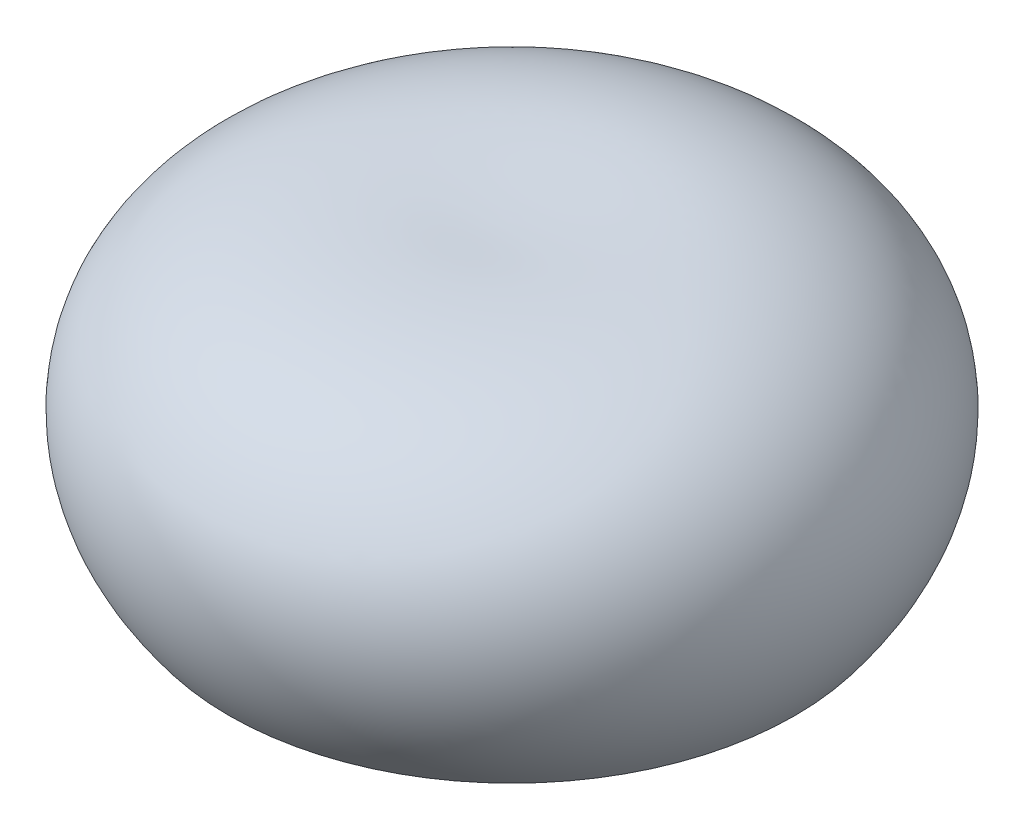
SolidWorks part; units mm, degrees
ref_plane "前视基准面" through (0, 0, 0) normal (0, 0, 1) x (1, 0, 0)
ref_plane "上视基准面" through (0, 0, 0) normal (0, 1, 0) x (1, 0, 0)
ref_plane "右视基准面" through (0, 0, 0) normal (1, 0, 0) x (0, 0, -1)
curve "曲线1"
  spline degree 3 poles (0, 7, 0) (0.0738, 6.9996, 0) (0.1783, 6.9991, 0) (0.3064, 7.0012, 0) (0.3805, 7.0029, 0) (0.4416, 7.0045, 0) (0.495, 7.0061, 0) (0.5432, 7.0077, 0) (0.5875, 7.0093, 0) (0.6288, 7.0109, 0) (0.6676, 7.0125, 0) (0.7044, 7.0141, 0) (0.7394, 7.0157, 0) (0.7729, 7.0172, 0) (0.8051, 7.0187, 0) (0.8362, 7.0203, 0) (0.8662, 7.0218, 0) (0.8953, 7.0233, 0) (0.9235, 7.0247, 0) (0.951, 7.0262, 0) (0.9778, 7.0276, 0) (1.004, 7.0291, 0) (1.0295, 7.0305, 0) (1.0545, 7.0319, 0) (1.079, 7.0333, 0) (1.103, 7.0346, 0) (1.1265, 7.036, 0) (1.1496, 7.0373, 0) (1.1724, 7.0386, 0) (1.1947, 7.0399, 0) (1.2167, 7.0412, 0) (1.2384, 7.0425, 0) (1.2598, 7.0438, 0) (1.2808, 7.045, 0) (1.3016, 7.0462, 0) (1.3221, 7.0474, 0) (1.3423, 7.0486, 0) (1.3623, 7.0498, 0) (1.382, 7.051, 0) (1.4015, 7.0521, 0) (1.4208, 7.0533, 0) (1.4399, 7.0544, 0) (1.4588, 7.0555, 0) (1.4775, 7.0566, 0) (1.496, 7.0577, 0) (1.5143, 7.0587, 0) (1.5324, 7.0598, 0) (1.5504, 7.0608, 0) (1.5682, 7.0618, 0) (1.5859, 7.0628, 0) (1.6034, 7.0638, 0) (1.6207, 7.0648, 0) (1.6379, 7.0657, 0) (1.655, 7.0667, 0) (1.672, 7.0676, 0) (1.6888, 7.0685, 0) (1.7054, 7.0694, 0) (1.722, 7.0703, 0) (1.7385, 7.0712, 0) (1.7548, 7.072, 0) (1.771, 7.0728, 0) (1.7871, 7.0737, 0) (1.8031, 7.0745, 0) (1.819, 7.0753, 0) (1.8348, 7.0761, 0) (1.8505, 7.0768, 0) (1.8661, 7.0776, 0) (1.8816, 7.0783, 0) (1.897, 7.079, 0) (1.9123, 7.0797, 0) (1.9275, 7.0804, 0) (1.9427, 7.0811, 0) (1.9578, 7.0818, 0) (1.9727, 7.0824, 0) (1.9876, 7.0831, 0) (2.0025, 7.0837, 0) (2.0172, 7.0843, 0) (2.0319, 7.0849, 0) (2.0465, 7.0855, 0) (2.061, 7.0861, 0) (2.0755, 7.0866, 0) (2.0899, 7.0872, 0) (2.1042, 7.0877, 0) (2.1184, 7.0882, 0) (2.1326, 7.0887, 0) (2.1468, 7.0892, 0) (2.1608, 7.0896, 0) (2.1748, 7.0901, 0) (2.1888, 7.0905, 0) (2.2027, 7.091, 0) (2.2165, 7.0914, 0) (2.2302, 7.0918, 0) (2.244, 7.0922, 0) (2.2576, 7.0925, 0) (2.2712, 7.0929, 0) (2.2848, 7.0933, 0) (2.2983, 7.0936, 0) (2.3117, 7.0939, 0) (2.3251, 7.0942, 0) (2.3385, 7.0945, 0) (2.3518, 7.0948, 0) (2.365, 7.095, 0) (2.3782, 7.0953, 0) (2.3914, 7.0955, 0) (2.4045, 7.0958, 0) (2.4175, 7.096, 0) (2.4305, 7.0962, 0) (2.4435, 7.0964, 0) (2.4565, 7.0965, 0) (2.4693, 7.0967, 0) (2.4822, 7.0968, 0) (2.495, 7.097, 0) (2.5078, 7.0971, 0) (2.5205, 7.0972, 0) (2.5332, 7.0973, 0) (2.5458, 7.0974, 0) (2.5584, 7.0974, 0) (2.571, 7.0975, 0) (2.5835, 7.0975, 0) (2.596, 7.0975, 0) (2.6085, 7.0975, 0) (2.6209, 7.0975, 0) (2.6333, 7.0975, 0) (2.6457, 7.0975, 0) (2.658, 7.0975, 0) (2.6703, 7.0974, 0) (2.6825, 7.0973, 0) (2.6948, 7.0973, 0) (2.7069, 7.0972, 0) (2.7191, 7.0971, 0) (2.7312, 7.0969, 0) (2.7433, 7.0968, 0) (2.7554, 7.0967, 0) (2.7674, 7.0965, 0) (2.7794, 7.0963, 0) (2.7914, 7.0962, 0) (2.8033, 7.096, 0) (2.8152, 7.0958, 0) (2.8271, 7.0955, 0) (2.8389, 7.0953, 0) (2.8508, 7.095, 0) (2.8625, 7.0948, 0) (2.8743, 7.0945, 0) (2.8861, 7.0942, 0) (2.8978, 7.0939, 0) (2.9094, 7.0936, 0) (2.9211, 7.0933, 0) (2.9327, 7.093, 0) (2.9443, 7.0926, 0) (2.9559, 7.0922, 0) (2.9675, 7.0919, 0) (2.979, 7.0915, 0) (2.9905, 7.0911, 0) (3.002, 7.0907, 0) (3.0134, 7.0902, 0) (3.0249, 7.0898, 0) (3.0363, 7.0893, 0) (3.0477, 7.0889, 0) (3.059, 7.0884, 0) (3.0704, 7.0879, 0) (3.0817, 7.0874, 0) (3.093, 7.0869, 0) (3.1042, 7.0864, 0) (3.1155, 7.0858, 0) (3.1267, 7.0853, 0) (3.1379, 7.0847, 0) (3.1491, 7.0841, 0) (3.1602, 7.0835, 0) (3.1714, 7.0829, 0) (3.1825, 7.0823, 0) (3.1936, 7.0817, 0) (3.2047, 7.0811, 0) (3.2157, 7.0804, 0) (3.2267, 7.0797, 0) (3.2378, 7.0791, 0) (3.2488, 7.0784, 0) (3.2597, 7.0777, 0) (3.2707, 7.0769, 0) (3.2816, 7.0762, 0) (3.2925, 7.0755, 0) (3.3034, 7.0747, 0) (3.3143, 7.074, 0) (3.3252, 7.0732, 0) (3.336, 7.0724, 0) (3.3468, 7.0716, 0) (3.3576, 7.0708, 0) (3.3684, 7.0699, 0) (3.3792, 7.0691, 0) (3.3899, 7.0683, 0) (3.4006, 7.0674, 0) (3.4113, 7.0665, 0) (3.422, 7.0656, 0) (3.4327, 7.0647, 0) (3.4434, 7.0638, 0) (3.454, 7.0629, 0) (3.4646, 7.0619, 0) (3.4752, 7.061, 0) (3.4858, 7.06, 0) (3.4964, 7.059, 0) (3.507, 7.0581, 0) (3.5175, 7.0571, 0) (3.528, 7.056, 0) (3.5385, 7.055, 0) (3.549, 7.054, 0) (3.5595, 7.0529, 0) (3.5699, 7.0519, 0) (3.5804, 7.0508, 0) (3.5908, 7.0497, 0) (3.6012, 7.0486, 0) (3.6116, 7.0475, 0) (3.622, 7.0464, 0) (3.6324, 7.0452, 0) (3.6427, 7.0441, 0) (3.6531, 7.0429, 0) (3.6634, 7.0417, 0) (3.6737, 7.0406, 0) (3.684, 7.0394, 0) (3.6942, 7.0381, 0) (3.7045, 7.0369, 0) (3.7148, 7.0357, 0) (3.725, 7.0344, 0) (3.7352, 7.0332, 0) (3.7454, 7.0319, 0) (3.7556, 7.0306, 0) (3.7658, 7.0293, 0) (3.7759, 7.028, 0) (3.7861, 7.0267, 0) (3.7962, 7.0254, 0) (3.8063, 7.024, 0) (3.8164, 7.0227, 0) (3.8265, 7.0213, 0) (3.8366, 7.0199, 0) (3.8467, 7.0185, 0) (3.8567, 7.0171, 0) (3.8668, 7.0157, 0) (3.8768, 7.0142, 0) (3.8868, 7.0128, 0) (3.8968, 7.0113, 0) (3.9068, 7.0099, 0) (3.9168, 7.0084, 0) (3.9267, 7.0069, 0) (3.9367, 7.0054, 0) (3.9466, 7.0039, 0) (3.9565, 7.0024, 0) (3.9665, 7.0008, 0) (3.9764, 6.9993, 0) (3.9862, 6.9977, 0) (3.9961, 6.9961, 0) (4.006, 6.9945, 0) (4.0158, 6.9929, 0) (4.0257, 6.9913, 0) (4.0355, 6.9897, 0) (4.0453, 6.988, 0) (4.0551, 6.9864, 0) (4.0649, 6.9847, 0) (4.0747, 6.983, 0) (4.0844, 6.9813, 0) (4.0942, 6.9796, 0) (4.1039, 6.9779, 0) (4.1136, 6.9762, 0) (4.1234, 6.9745, 0) (4.1331, 6.9727, 0) (4.1428, 6.971, 0) (4.1524, 6.9692, 0) (4.1621, 6.9674, 0) (4.1718, 6.9656, 0) (4.1814, 6.9638, 0) (4.1911, 6.962, 0) (4.2007, 6.9601, 0) (4.2103, 6.9583, 0) (4.2199, 6.9564, 0) (4.2295, 6.9545, 0) (4.2391, 6.9527, 0) (4.2486, 6.9508, 0) (4.2582, 6.9488, 0) (4.2677, 6.9469, 0) (4.2773, 6.945, 0) (4.2868, 6.943, 0) (4.2963, 6.9411, 0) (4.3058, 6.9391, 0) (4.3153, 6.9371, 0) (4.3248, 6.9351, 0) (4.3343, 6.9331, 0) (4.3437, 6.9311, 0) (4.3532, 6.9291, 0) (4.3626, 6.927, 0) (4.3721, 6.925, 0) (4.3815, 6.9229, 0) (4.3909, 6.9208, 0) (4.4003, 6.9187, 0) (4.4097, 6.9166, 0) (4.4191, 6.9145, 0) (4.4284, 6.9123, 0) (4.4378, 6.9102, 0) (4.4471, 6.908, 0) (4.4565, 6.9059, 0) (4.4658, 6.9037, 0) (4.4751, 6.9015, 0) (4.4844, 6.8993, 0) (4.4937, 6.8971, 0) (4.503, 6.8948, 0) (4.5123, 6.8926, 0) (4.5215, 6.8903, 0) (4.5308, 6.8881, 0) (4.54, 6.8858, 0) (4.5493, 6.8835, 0) (4.5585, 6.8812, 0) (4.5677, 6.8789, 0) (4.5769, 6.8765, 0) (4.5861, 6.8742, 0) (4.5953, 6.8718, 0) (4.6045, 6.8695, 0) (4.6136, 6.8671, 0) (4.6228, 6.8647, 0) (4.6319, 6.8623, 0) (4.6411, 6.8599, 0) (4.6502, 6.8575, 0) (4.6593, 6.855, 0) (4.6684, 6.8526, 0) (4.6775, 6.8501, 0) (4.6866, 6.8476, 0) (4.6957, 6.8451, 0) (4.7048, 6.8426, 0) (4.7138, 6.8401, 0) (4.7229, 6.8376, 0) (4.7319, 6.835, 0) (4.741, 6.8325, 0) (4.75, 6.8299, 0) (4.759, 6.8273, 0) (4.768, 6.8247, 0) (4.777, 6.8221, 0) (4.786, 6.8195, 0) (4.795, 6.8169, 0) (4.8039, 6.8142, 0) (4.8129, 6.8116, 0) (4.8218, 6.8089, 0) (4.8308, 6.8062, 0) (4.8397, 6.8035, 0) (4.8486, 6.8008, 0) (4.8575, 6.7981, 0) (4.8664, 6.7954, 0) (4.8753, 6.7926, 0) (4.8842, 6.7899, 0) (4.8931, 6.7871, 0) (4.902, 6.7843, 0) (4.9108, 6.7815, 0) (4.9197, 6.7787, 0) (4.9285, 6.7759, 0) (4.9373, 6.7731, 0) (4.9462, 6.7702, 0) (4.955, 6.7673, 0) (4.9638, 6.7645, 0) (4.9726, 6.7616, 0) (4.9813, 6.7587, 0) (4.9901, 6.7558, 0) (4.9989, 6.7529, 0) (5.0076, 6.7499, 0) (5.0164, 6.747, 0) (5.0251, 6.744, 0) (5.0339, 6.7411, 0) (5.0426, 6.7381, 0) (5.0513, 6.7351, 0) (5.06, 6.7321, 0) (5.0687, 6.729, 0) (5.0774, 6.726, 0) (5.0861, 6.7229, 0) (5.0947, 6.7199, 0) (5.1034, 6.7168, 0) (5.112, 6.7137, 0) (5.1207, 6.7106, 0) (5.1293, 6.7075, 0) (5.1379, 6.7044, 0) (5.1465, 6.7012, 0) (5.1552, 6.6981, 0) (5.1638, 6.6949, 0) (5.1723, 6.6917, 0) (5.1809, 6.6885, 0) (5.1895, 6.6853, 0) (5.1981, 6.6821, 0) (5.2066, 6.6789, 0) (5.2151, 6.6756, 0) (5.2237, 6.6724, 0) (5.2322, 6.6691, 0) (5.2407, 6.6658, 0) (5.2492, 6.6625, 0) (5.2577, 6.6592, 0) (5.2662, 6.6559, 0) (5.2747, 6.6526, 0) (5.2832, 6.6492, 0) (5.2917, 6.6459, 0) (5.3001, 6.6425, 0) (5.3086, 6.6391, 0) (5.317, 6.6357, 0) (5.3254, 6.6323, 0) (5.3338, 6.6289, 0) (5.3423, 6.6254, 0) (5.3507, 6.622, 0) (5.3591, 6.6185, 0) (5.3674, 6.615, 0) (5.3758, 6.6115, 0) (5.3842, 6.608, 0) (5.3926, 6.6045, 0) (5.4009, 6.601, 0) (5.4092, 6.5974, 0) (5.4176, 6.5939, 0) (5.4259, 6.5903, 0) (5.4342, 6.5867, 0) (5.4425, 6.5831, 0) (5.4508, 6.5795, 0) (5.4591, 6.5759, 0) (5.4674, 6.5722, 0) (5.4757, 6.5686, 0) (5.4839, 6.5649, 0) (5.4922, 6.5612, 0) (5.5004, 6.5576, 0) (5.5087, 6.5538, 0) (5.5169, 6.5501, 0) (5.5251, 6.5464, 0) (5.5333, 6.5427, 0) (5.5415, 6.5389, 0) (5.5497, 6.5351, 0) (5.5579, 6.5313, 0) (5.5661, 6.5275, 0) (5.5743, 6.5237, 0) (5.5824, 6.5199, 0) (5.5906, 6.5161, 0) (5.5987, 6.5122, 0) (5.6069, 6.5083, 0) (5.615, 6.5045, 0) (5.6231, 6.5006, 0) (5.6312, 6.4967, 0) (5.6393, 6.4927, 0) (5.6474, 6.4888, 0) (5.6555, 6.4849, 0) (5.6635, 6.4809, 0) (5.6716, 6.4769, 0) (5.6796, 6.4729, 0) (5.6877, 6.4689, 0) (5.6957, 6.4649, 0) (5.7038, 6.4609, 0) (5.7118, 6.4568, 0) (5.7198, 6.4528, 0) (5.7278, 6.4487, 0) (5.7358, 6.4446, 0) (5.7438, 6.4405, 0) (5.7517, 6.4364, 0) (5.7597, 6.4323, 0) (5.7676, 6.4282, 0) (5.7756, 6.424, 0) (5.7835, 6.4198, 0) (5.7915, 6.4157, 0) (5.7994, 6.4115, 0) (5.8073, 6.4073, 0) (5.8152, 6.403, 0) (5.8231, 6.3988, 0) (5.831, 6.3945, 0) (5.8388, 6.3903, 0) (5.8467, 6.386, 0) (5.8546, 6.3817, 0) (5.8624, 6.3774, 0) (5.8703, 6.3731, 0) (5.8781, 6.3687, 0) (5.8859, 6.3644, 0) (5.8937, 6.36, 0) (5.9015, 6.3557, 0) (5.9093, 6.3513, 0) (5.9171, 6.3469, 0) (5.9249, 6.3424, 0) (5.9326, 6.338, 0) (5.9404, 6.3336, 0) (5.9481, 6.3291, 0) (5.9559, 6.3246, 0) (5.9636, 6.3201, 0) (5.9713, 6.3156, 0) (5.979, 6.3111, 0) (5.9867, 6.3066, 0) (5.9944, 6.302, 0) (6.0021, 6.2975, 0) (6.0098, 6.2929, 0) (6.0175, 6.2883, 0) (6.0251, 6.2837, 0) (6.0328, 6.2791, 0) (6.0404, 6.2745, 0) (6.048, 6.2698, 0) (6.0556, 6.2652, 0) (6.0633, 6.2605, 0) (6.0709, 6.2558, 0) (6.0784, 6.2511, 0) (6.086, 6.2464, 0) (6.0936, 6.2416, 0) (6.1012, 6.2369, 0) (6.1087, 6.2321, 0) (6.1163, 6.2274, 0) (6.1238, 6.2226, 0) (6.1313, 6.2178, 0) (6.1388, 6.2129, 0) (6.1463, 6.2081, 0) (6.1538, 6.2033, 0) (6.1613, 6.1984, 0) (6.1688, 6.1935, 0) (6.1763, 6.1886, 0) (6.1837, 6.1837, 0) (6.1912, 6.1788, 0) (6.1986, 6.1739, 0) (6.206, 6.1689, 0) (6.2134, 6.1639, 0) (6.2208, 6.159, 0) (6.2282, 6.154, 0) (6.2356, 6.1489, 0) (6.243, 6.1439, 0) (6.2504, 6.1389, 0) (6.2577, 6.1338, 0) (6.2651, 6.1287, 0) (6.2724, 6.1237, 0) (6.2798, 6.1186, 0) (6.2871, 6.1134, 0) (6.2944, 6.1083, 0) (6.3017, 6.1032, 0) (6.309, 6.098, 0) (6.3163, 6.0928, 0) (6.3235, 6.0876, 0) (6.3308, 6.0824, 0) (6.3381, 6.0772, 0) (6.3453, 6.072, 0) (6.3525, 6.0667, 0) (6.3598, 6.0615, 0) (6.367, 6.0562, 0) (6.3742, 6.0509, 0) (6.3814, 6.0456, 0) (6.3885, 6.0403, 0) (6.3957, 6.0349, 0) (6.4029, 6.0296, 0) (6.41, 6.0242, 0) (6.4172, 6.0188, 0) (6.4243, 6.0134, 0) (6.4314, 6.008, 0) (6.4385, 6.0025, 0) (6.4456, 5.9971, 0) (6.4527, 5.9916, 0) (6.4598, 5.9861, 0) (6.4668, 5.9806, 0) (6.4739, 5.9751, 0) (6.4809, 5.9696, 0) (6.488, 5.9641, 0) (6.495, 5.9585, 0) (6.502, 5.9529, 0) (6.509, 5.9473, 0) (6.516, 5.9417, 0) (6.523, 5.9361, 0) (6.53, 5.9305, 0) (6.5369, 5.9248, 0) (6.5439, 5.9192, 0) (6.5508, 5.9135, 0) (6.5578, 5.9078, 0) (6.5647, 5.9021, 0) (6.5716, 5.8963, 0) (6.5785, 5.8906, 0) (6.5854, 5.8848, 0) (6.5922, 5.8791, 0) (6.5991, 5.8733, 0) (6.606, 5.8675, 0) (6.6128, 5.8616, 0) (6.6196, 5.8558, 0) (6.6265, 5.8499, 0) (6.6333, 5.8441, 0) (6.6401, 5.8382, 0) (6.6469, 5.8323, 0) (6.6536, 5.8263, 0) (6.6604, 5.8204, 0) (6.6672, 5.8144, 0) (6.6739, 5.8085, 0) (6.6806, 5.8025, 0) (6.6874, 5.7965, 0) (6.6941, 5.7905, 0) (6.7008, 5.7844, 0) (6.7074, 5.7784, 0) (6.7141, 5.7723, 0) (6.7208, 5.7662, 0) (6.7274, 5.7601, 0) (6.7341, 5.754, 0) (6.7407, 5.7479, 0) (6.7473, 5.7417, 0) (6.7539, 5.7356, 0) (6.7605, 5.7294, 0) (6.7671, 5.7232, 0) (6.7737, 5.717, 0) (6.7802, 5.7107, 0) (6.7868, 5.7045, 0) (6.7933, 5.6982, 0) (6.7998, 5.6919, 0) (6.8064, 5.6856, 0) (6.8129, 5.6793, 0) (6.8194, 5.673, 0) (6.8258, 5.6666, 0) (6.8323, 5.6603, 0) (6.8387, 5.6539, 0) (6.8452, 5.6475, 0) (6.8516, 5.6411, 0) (6.858, 5.6346, 0) (6.8644, 5.6282, 0) (6.8708, 5.6217, 0) (6.8772, 5.6152, 0) (6.8836, 5.6087, 0) (6.8899, 5.6022, 0) (6.8963, 5.5957, 0) (6.9026, 5.5891, 0) (6.9089, 5.5825, 0) (6.9152, 5.5759, 0) (6.9215, 5.5693, 0) (6.9278, 5.5627, 0) (6.9341, 5.5561, 0) (6.9403, 5.5494, 0) (6.9466, 5.5427, 0) (6.9528, 5.5361, 0) (6.959, 5.5293, 0) (6.9652, 5.5226, 0) (6.9714, 5.5159, 0) (6.9776, 5.5091, 0) (6.9838, 5.5023, 0) (6.9899, 5.4955, 0) (6.9961, 5.4887, 0) (7.0022, 5.4819, 0) (7.0083, 5.475, 0) (7.0144, 5.4682, 0) (7.0205, 5.4613, 0) (7.0266, 5.4544, 0) (7.0326, 5.4475, 0) (7.0387, 5.4405, 0) (7.0447, 5.4336, 0) (7.0507, 5.4266, 0) (7.0568, 5.4196, 0) (7.0627, 5.4126, 0) (7.0687, 5.4055, 0) (7.0747, 5.3985, 0) (7.0807, 5.3914, 0) (7.0866, 5.3844, 0) (7.0925, 5.3772, 0) (7.0984, 5.3701, 0) (7.1043, 5.363, 0) (7.1102, 5.3558, 0) (7.1161, 5.3487, 0) (7.122, 5.3415, 0) (7.1278, 5.3343, 0) (7.1336, 5.327, 0) (7.1395, 5.3198, 0) (7.1453, 5.3125, 0) (7.151, 5.3052, 0) (7.1568, 5.2979, 0) (7.1626, 5.2906, 0) (7.1683, 5.2833, 0) (7.1741, 5.2759, 0) (7.1798, 5.2685, 0) (7.1855, 5.2611, 0) (7.1912, 5.2537, 0) (7.1968, 5.2463, 0) (7.2025, 5.2388, 0) (7.2082, 5.2313, 0) (7.2138, 5.2238, 0) (7.2194, 5.2163, 0) (7.225, 5.2088, 0) (7.2306, 5.2013, 0) (7.2362, 5.1937, 0) (7.2417, 5.1861, 0) (7.2473, 5.1785, 0) (7.2528, 5.1709, 0) (7.2583, 5.1632, 0) (7.2638, 5.1556, 0) (7.2693, 5.1479, 0) (7.2748, 5.1402, 0) (7.2802, 5.1324, 0) (7.2856, 5.1247, 0) (7.2911, 5.1169, 0) (7.2965, 5.1092, 0) (7.3019, 5.1014, 0) (7.3072, 5.0935, 0) (7.3126, 5.0857, 0) (7.3179, 5.0778, 0) (7.3233, 5.0699, 0) (7.3286, 5.062, 0) (7.3339, 5.0541, 0) (7.3391, 5.0462, 0) (7.3444, 5.0382, 0) (7.3497, 5.0302, 0) (7.3549, 5.0222, 0) (7.3601, 5.0142, 0) (7.3653, 5.0062, 0) (7.3705, 4.9981, 0) (7.3757, 4.99, 0) (7.3808, 4.9819, 0) (7.3859, 4.9738, 0) (7.3911, 4.9657, 0) (7.3962, 4.9575, 0) (7.4012, 4.9493, 0) (7.4063, 4.9411, 0) (7.4114, 4.9329, 0) (7.4164, 4.9246, 0) (7.4214, 4.9164, 0) (7.4264, 4.9081, 0) (7.4314, 4.8998, 0) (7.4364, 4.8914, 0) (7.4413, 4.8831, 0) (7.4462, 4.8747, 0) (7.4512, 4.8663, 0) (7.4561, 4.8579, 0) (7.4609, 4.8495, 0) (7.4658, 4.841, 0) (7.4706, 4.8325, 0) (7.4755, 4.824, 0) (7.4803, 4.8155, 0) (7.4851, 4.807, 0) (7.4899, 4.7984, 0) (7.4946, 4.7898, 0) (7.4993, 4.7812, 0) (7.5041, 4.7726, 0) (7.5088, 4.7639, 0) (7.5134, 4.7552, 0) (7.5181, 4.7465, 0) (7.5228, 4.7378, 0) (7.5274, 4.7291, 0) (7.532, 4.7203, 0) (7.5366, 4.7115, 0) (7.5412, 4.7027, 0) (7.5457, 4.6939, 0) (7.5503, 4.6851, 0) (7.5548, 4.6762, 0) (7.5593, 4.6673, 0) (7.5637, 4.6584, 0) (7.5682, 4.6494, 0) (7.5726, 4.6405, 0) (7.5771, 4.6315, 0) (7.5815, 4.6225, 0) (7.5858, 4.6134, 0) (7.5902, 4.6044, 0) (7.5945, 4.5953, 0) (7.5989, 4.5862, 0) (7.6032, 4.5771, 0) (7.6075, 4.5679, 0) (7.6117, 4.5587, 0) (7.616, 4.5495, 0) (7.6202, 4.5403, 0) (7.6244, 4.5311, 0) (7.6286, 4.5218, 0) (7.6327, 4.5125, 0) (7.6369, 4.5032, 0) (7.641, 4.4939, 0) (7.6451, 4.4845, 0) (7.6492, 4.4751, 0) (7.6532, 4.4657, 0) (7.6573, 4.4563, 0) (7.6613, 4.4468, 0) (7.6653, 4.4373, 0) (7.6692, 4.4278, 0) (7.6732, 4.4183, 0) (7.6771, 4.4087, 0) (7.681, 4.3992, 0) (7.6849, 4.3896, 0) (7.6888, 4.3799, 0) (7.6926, 4.3703, 0) (7.6964, 4.3606, 0) (7.7002, 4.3509, 0) (7.704, 4.3411, 0) (7.7078, 4.3314, 0) (7.7115, 4.3216, 0) (7.7152, 4.3118, 0) (7.7189, 4.302, 0) (7.7226, 4.2921, 0) (7.7262, 4.2822, 0) (7.7298, 4.2723, 0) (7.7334, 4.2624, 0) (7.737, 4.2524, 0) (7.7405, 4.2424, 0) (7.744, 4.2324, 0) (7.7475, 4.2223, 0) (7.751, 4.2123, 0) (7.7545, 4.2022, 0) (7.7579, 4.1921, 0) (7.7613, 4.1819, 0) (7.7647, 4.1717, 0) (7.768, 4.1615, 0) (7.7714, 4.1513, 0) (7.7747, 4.141, 0) (7.778, 4.1308, 0) (7.7812, 4.1204, 0) (7.7845, 4.1101, 0) (7.7877, 4.0997, 0) (7.7908, 4.0893, 0) (7.794, 4.0789, 0) (7.7971, 4.0685, 0) (7.8002, 4.058, 0) (7.8033, 4.0475, 0) (7.8064, 4.0369, 0) (7.8094, 4.0264, 0) (7.8124, 4.0158, 0) (7.8154, 4.0051, 0) (7.8183, 3.9945, 0) (7.8212, 3.9838, 0) (7.8241, 3.9731, 0) (7.827, 3.9624, 0) (7.8298, 3.9516, 0) (7.8327, 3.9408, 0) (7.8354, 3.93, 0) (7.8382, 3.9191, 0) (7.8409, 3.9082, 0) (7.8436, 3.8973, 0) (7.8463, 3.8863, 0) (7.849, 3.8754, 0) (7.8516, 3.8643, 0) (7.8542, 3.8533, 0) (7.8567, 3.8422, 0) (7.8593, 3.8311, 0) (7.8618, 3.82, 0) (7.8642, 3.8088, 0) (7.8667, 3.7976, 0) (7.8691, 3.7864, 0) (7.8715, 3.7751, 0) (7.8738, 3.7638, 0) (7.8762, 3.7525, 0) (7.8785, 3.7411, 0) (7.8807, 3.7297, 0) (7.883, 3.7183, 0) (7.8852, 3.7069, 0) (7.8873, 3.6954, 0) (7.8895, 3.6838, 0) (7.8916, 3.6723, 0) (7.8937, 3.6607, 0) (7.8957, 3.6491, 0) (7.8977, 3.6374, 0) (7.8997, 3.6257, 0) (7.9016, 3.614, 0) (7.9036, 3.6022, 0) (7.9054, 3.5904, 0) (7.9073, 3.5786, 0) (7.9091, 3.5667, 0) (7.9109, 3.5548, 0) (7.9126, 3.5429, 0) (7.9144, 3.5309, 0) (7.916, 3.5189, 0) (7.9177, 3.5068, 0) (7.9193, 3.4947, 0) (7.9209, 3.4826, 0) (7.9224, 3.4705, 0) (7.9239, 3.4583, 0) (7.9254, 3.446, 0) (7.9268, 3.4338, 0) (7.9282, 3.4214, 0) (7.9296, 3.4091, 0) (7.9309, 3.3967, 0) (7.9322, 3.3843, 0) (7.9334, 3.3718, 0) (7.9346, 3.3593, 0) (7.9358, 3.3468, 0) (7.9369, 3.3342, 0) (7.938, 3.3215, 0) (7.9391, 3.3089, 0) (7.9401, 3.2962, 0) (7.9411, 3.2834, 0) (7.942, 3.2706, 0) (7.9429, 3.2578, 0) (7.9438, 3.2449, 0) (7.9446, 3.232, 0) (7.9454, 3.219, 0) (7.9461, 3.206, 0) (7.9468, 3.193, 0) (7.9475, 3.1799, 0) (7.9481, 3.1668, 0) (7.9486, 3.1536, 0) (7.9492, 3.1403, 0) (7.9496, 3.1271, 0) (7.9501, 3.1138, 0) (7.9505, 3.1004, 0) (7.9508, 3.087, 0) (7.9511, 3.0735, 0) (7.9514, 3.06, 0) (7.9516, 3.0465, 0) (7.9517, 3.0329, 0) (7.9518, 3.0192, 0) (7.9519, 3.0055, 0) (7.9519, 2.9918, 0) (7.9519, 2.978, 0) (7.9518, 2.9641, 0) (7.9517, 2.9502, 0) (7.9515, 2.9363, 0) (7.9513, 2.9223, 0) (7.951, 2.9082, 0) (7.9507, 2.8941, 0) (7.9503, 2.88, 0) (7.9499, 2.8657, 0) (7.9494, 2.8515, 0) (7.9489, 2.8371, 0) (7.9483, 2.8228, 0) (7.9477, 2.8083, 0) (7.947, 2.7938, 0) (7.9462, 2.7793, 0) (7.9454, 2.7647, 0) (7.9445, 2.75, 0) (7.9436, 2.7353, 0) (7.9426, 2.7205, 0) (7.9416, 2.7056, 0) (7.9405, 2.6907, 0) (7.9393, 2.6757, 0) (7.9381, 2.6607, 0) (7.9368, 2.6456, 0) (7.9355, 2.6304, 0) (7.9341, 2.6152, 0) (7.9326, 2.5999, 0) (7.9311, 2.5845, 0) (7.9295, 2.5691, 0) (7.9278, 2.5536, 0) (7.9261, 2.538, 0) (7.9243, 2.5224, 0) (7.9224, 2.5066, 0) (7.9205, 2.4909, 0) (7.9185, 2.475, 0) (7.9164, 2.459, 0) (7.9143, 2.443, 0) (7.912, 2.4269, 0) (7.9097, 2.4108, 0) (7.9074, 2.3945, 0) (7.9049, 2.3782, 0) (7.9024, 2.3618, 0) (7.8998, 2.3453, 0) (7.8971, 2.3287, 0) (7.8943, 2.312, 0) (7.8915, 2.2953, 0) (7.8885, 2.2784, 0) (7.8855, 2.2615, 0) (7.8824, 2.2445, 0) (7.8792, 2.2273, 0) (7.8759, 2.2101, 0) (7.8725, 2.1928, 0) (7.8691, 2.1754, 0) (7.8655, 2.1579, 0) (7.8618, 2.1403, 0) (7.8581, 2.1225, 0) (7.8542, 2.1047, 0) (7.8503, 2.0868, 0) (7.8462, 2.0687, 0) (7.842, 2.0506, 0) (7.8378, 2.0323, 0) (7.8334, 2.0139, 0) (7.8289, 1.9954, 0) (7.8243, 1.9767, 0) (7.8195, 1.9579, 0) (7.8147, 1.939, 0) (7.8097, 1.92, 0) (7.8046, 1.9008, 0) (7.7994, 1.8815, 0) (7.794, 1.8621, 0) (7.7885, 1.8425, 0) (7.7829, 1.8227, 0) (7.7771, 1.8028, 0) (7.7712, 1.7828, 0) (7.7652, 1.7626, 0) (7.759, 1.7422, 0) (7.7526, 1.7216, 0) (7.7461, 1.7009, 0) (7.7394, 1.6799, 0) (7.7325, 1.6588, 0) (7.7255, 1.6375, 0) (7.7182, 1.616, 0) (7.7108, 1.5943, 0) (7.7032, 1.5723, 0) (7.6954, 1.5502, 0) (7.6874, 1.5278, 0) (7.6792, 1.5051, 0) (7.6708, 1.4822, 0) (7.6621, 1.4591, 0) (7.6532, 1.4357, 0) (7.644, 1.412, 0) (7.6346, 1.388, 0) (7.6249, 1.3637, 0) (7.615, 1.3391, 0) (7.6047, 1.3141, 0) (7.5941, 1.2888, 0) (7.5833, 1.2631, 0) (7.572, 1.237, 0) (7.5604, 1.2105, 0) (7.5485, 1.1835, 0) (7.5361, 1.1561, 0) (7.5233, 1.1282, 0) (7.51, 1.0997, 0) (7.4963, 1.0707, 0) (7.482, 1.041, 0) (7.4672, 1.0107, 0) (7.4518, 0.9797, 0) (7.4357, 0.9478, 0) (7.4189, 0.9152, 0) (7.4013, 0.8815, 0) (7.3829, 0.8469, 0) (7.3635, 0.811, 0) (7.343, 0.7739, 0) (7.3212, 0.7352, 0) (7.2981, 0.6948, 0) (7.2732, 0.6523, 0) (7.2464, 0.6073, 0) (7.2172, 0.5594, 0) (7.1849, 0.5076, 0) (7.1485, 0.4506, 0) (7.1062, 0.386, 0) (7.0539, 0.3086, 0) (6.9626, 0.1779, 0) (6.8856, 0.0734, 0) (6.8314, 0, 0) knots 0 0 0 0 0.016508 0.023364 0.028636 0.033092 0.037026 0.040591 0.043877 0.046942 0.049828 0.052563 0.055171 0.057668 0.060068 0.062382 0.06462 0.066789 0.068896 0.070946 0.072944 0.074894 0.0768 0.078664 0.080491 0.082282 0.08404 0.085766 0.087463 0.089131 0.090774 0.092392 0.093986 0.095557 0.097107 0.098637 0.100147 0.101639 0.103112 0.104569 0.10601 0.107434 0.108844 0.110239 0.11162 0.112987 0.114341 0.115683 0.117013 0.118331 0.119637 0.120933 0.122218 0.123492 0.124757 0.126012 0.127257 0.128493 0.129721 0.130939 0.132149 0.133351 0.134545 0.135731 0.13691 0.138081 0.139245 0.140402 0.141552 0.142695 0.143832 0.144962 0.146086 0.147204 0.148315 0.149421 0.150522 0.151616 0.152705 0.153789 0.154868 0.155941 0.157009 0.158072 0.159131 0.160184 0.161233 0.162277 0.163317 0.164352 0.165383 0.16641 0.167433 0.168451 0.169465 0.170476 0.171482 0.172485 0.173483 0.174478 0.17547 0.176457 0.177442 0.178422 0.1794 0.180374 0.181344 0.182312 0.183276 0.184236 0.185194 0.186149 0.187101 0.188049 0.188995 0.189938 0.190877 0.191815 0.192749 0.19368 0.194609 0.195535 0.196459 0.19738 0.198298 0.199214 0.200127 0.201038 0.201946 0.202852 0.203756 0.204657 0.205556 0.206453 0.207347 0.208239 0.209129 0.210017 0.210902 0.211786 0.212667 0.213547 0.214424 0.215299 0.216172 0.217044 0.217913 0.21878 0.219646 0.220509 0.221371 0.222231 0.223089 0.223945 0.2248 0.225652 0.226503 0.227353 0.2282 0.229046 0.22989 0.230732 0.231573 0.232412 0.23325 0.234086 0.23492 0.235753 0.236585 0.237414 0.238243 0.239069 0.239895 0.240719 0.241541 0.242362 0.243182 0.244 0.244816 0.245632 0.246446 0.247258 0.24807 0.24888 0.249688 0.250496 0.251302 0.252106 0.25291 0.253712 0.254513 0.255313 0.256111 0.256909 0.257705 0.2585 0.259294 0.260086 0.260878 0.261668 0.262457 0.263245 0.264032 0.264818 0.265603 0.266386 0.267169 0.26795 0.268731 0.26951 0.270288 0.271066 0.271842 0.272617 0.273391 0.274165 0.274937 0.275708 0.276478 0.277248 0.278016 0.278784 0.27955 0.280316 0.28108 0.281844 0.282607 0.283369 0.28413 0.28489 0.285649 0.286407 0.287165 0.287921 0.288677 0.289432 0.290186 0.290939 0.291692 0.292444 0.293194 0.293944 0.294693 0.295442 0.296189 0.296936 0.297682 0.298428 0.299172 0.299916 0.300659 0.301401 0.302143 0.302883 0.303624 0.304363 0.305101 0.305839 0.306577 0.307313 0.308049 0.308784 0.309518 0.310252 0.310985 0.311718 0.312449 0.31318 0.313911 0.31464 0.31537 0.316098 0.316826 0.317553 0.31828 0.319006 0.319731 0.320456 0.32118 0.321903 0.322626 0.323349 0.32407 0.324791 0.325512 0.326232 0.326951 0.32767 0.328389 0.329106 0.329824 0.33054 0.331256 0.331972 0.332687 0.333401 0.334115 0.334829 0.335541 0.336254 0.336966 0.337677 0.338388 0.339098 0.339808 0.340517 0.341226 0.341934 0.342642 0.34335 0.344057 0.344763 0.345469 0.346174 0.346879 0.347584 0.348288 0.348992 0.349695 0.350398 0.3511 0.351802 0.352503 0.353204 0.353905 0.354605 0.355305 0.356004 0.356703 0.357401 0.3581 0.358797 0.359494 0.360191 0.360888 0.361584 0.362279 0.362975 0.36367 0.364364 0.365058 0.365752 0.366445 0.367138 0.367831 0.368523 0.369215 0.369907 0.370598 0.371289 0.371979 0.372669 0.373359 0.374049 0.374738 0.375427 0.376115 0.376803 0.377491 0.378178 0.378866 0.379552 0.380239 0.380925 0.381611 0.382297 0.382982 0.383667 0.384351 0.385036 0.38572 0.386404 0.387087 0.38777 0.388453 0.389136 0.389818 0.3905 0.391182 0.391863 0.392545 0.393226 0.393906 0.394587 0.395267 0.395947 0.396627 0.397306 0.397985 0.398664 0.399343 0.400021 0.400699 0.401377 0.402055 0.402733 0.40341 0.404087 0.404764 0.40544 0.406117 0.406793 0.407469 0.408144 0.40882 0.409495 0.41017 0.410845 0.41152 0.412194 0.412868 0.413542 0.414216 0.41489 0.415563 0.416237 0.41691 0.417583 0.418255 0.418928 0.4196 0.420273 0.420945 0.421616 0.422288 0.42296 0.423631 0.424302 0.424973 0.425644 0.426315 0.426986 0.427656 0.428326 0.428997 0.429667 0.430336 0.431006 0.431676 0.432345 0.433015 0.433684 0.434353 0.435022 0.435691 0.436359 0.437028 0.437696 0.438365 0.439033 0.439701 0.440369 0.441037 0.441705 0.442373 0.44304 0.443708 0.444375 0.445043 0.44571 0.446377 0.447044 0.447711 0.448378 0.449045 0.449711 0.450378 0.451045 0.451711 0.452378 0.453044 0.45371 0.454377 0.455043 0.455709 0.456375 0.457041 0.457707 0.458373 0.459039 0.459705 0.460371 0.461036 0.461702 0.462368 0.463034 0.463699 0.464365 0.46503 0.465696 0.466361 0.467027 0.467692 0.468358 0.469023 0.469689 0.470354 0.47102 0.471685 0.472351 0.473016 0.473681 0.474347 0.475012 0.475678 0.476343 0.477009 0.477674 0.47834 0.479005 0.479671 0.480336 0.481002 0.481668 0.482333 0.482999 0.483665 0.48433 0.484996 0.485662 0.486328 0.486994 0.48766 0.488326 0.488992 0.489658 0.490324 0.490991 0.491657 0.492324 0.49299 0.493657 0.494323 0.49499 0.495657 0.496324 0.496991 0.497658 0.498325 0.498992 0.499659 0.500327 0.500994 0.501662 0.50233 0.502997 0.503665 0.504333 0.505001 0.50567 0.506338 0.507007 0.507675 0.508344 0.509013 0.509682 0.510351 0.511021 0.51169 0.51236 0.513029 0.513699 0.514369 0.515039 0.51571 0.51638 0.517051 0.517722 0.518393 0.519064 0.519735 0.520407 0.521078 0.52175 0.522422 0.523095 0.523767 0.52444 0.525113 0.525786 0.526459 0.527132 0.527806 0.52848 0.529154 0.529828 0.530502 0.531177 0.531852 0.532527 0.533203 0.533878 0.534554 0.53523 0.535907 0.536583 0.53726 0.537937 0.538614 0.539292 0.53997 0.540648 0.541327 0.542005 0.542684 0.543363 0.544043 0.544723 0.545403 0.546083 0.546764 0.547445 0.548126 0.548808 0.549489 0.550172 0.550854 0.551537 0.55222 0.552904 0.553587 0.554271 0.554956 0.555641 0.556326 0.557011 0.557697 0.558383 0.55907 0.559757 0.560444 0.561132 0.56182 0.562508 0.563197 0.563886 0.564576 0.565266 0.565956 0.566647 0.567338 0.568029 0.568721 0.569414 0.570107 0.5708 0.571493 0.572188 0.572882 0.573577 0.574272 0.574968 0.575665 0.576361 0.577059 0.577756 0.578454 0.579153 0.579852 0.580552 0.581252 0.581952 0.582653 0.583355 0.584057 0.58476 0.585463 0.586166 0.586871 0.587575 0.58828 0.588986 0.589692 0.590399 0.591107 0.591815 0.592523 0.593232 0.593942 0.594652 0.595363 0.596074 0.596786 0.597499 0.598212 0.598926 0.59964 0.600355 0.601071 0.601787 0.602504 0.603222 0.60394 0.604659 0.605379 0.606099 0.60682 0.607541 0.608264 0.608987 0.60971 0.610435 0.61116 0.611885 0.612612 0.613339 0.614067 0.614796 0.615525 0.616255 0.616986 0.617718 0.61845 0.619183 0.619917 0.620652 0.621388 0.622124 0.622861 0.623599 0.624338 0.625078 0.625818 0.62656 0.627302 0.628045 0.628789 0.629534 0.630279 0.631026 0.631773 0.632522 0.633271 0.634021 0.634772 0.635524 0.636277 0.637031 0.637786 0.638542 0.639299 0.640056 0.640815 0.641575 0.642336 0.643098 0.64386 0.644624 0.645389 0.646155 0.646922 0.64769 0.648459 0.64923 0.650001 0.650773 0.651547 0.652322 0.653098 0.653875 0.654653 0.655432 0.656212 0.656994 0.657777 0.658561 0.659346 0.660133 0.66092 0.661709 0.662499 0.663291 0.664084 0.664878 0.665673 0.66647 0.667268 0.668067 0.668868 0.66967 0.670473 0.671278 0.672084 0.672892 0.673701 0.674511 0.675323 0.676136 0.676951 0.677768 0.678585 0.679405 0.680225 0.681048 0.681872 0.682697 0.683524 0.684353 0.685183 0.686015 0.686849 0.687684 0.688521 0.689359 0.690199 0.691041 0.691885 0.692731 0.693578 0.694427 0.695278 0.69613 0.696985 0.697841 0.698699 0.699559 0.700421 0.701285 0.702151 0.703018 0.703888 0.70476 0.705634 0.706509 0.707387 0.708267 0.709149 0.710033 0.710919 0.711808 0.712698 0.713591 0.714486 0.715384 0.716283 0.717185 0.718089 0.718996 0.719905 0.720816 0.721729 0.722646 0.723564 0.724485 0.725409 0.726335 0.727264 0.728195 0.729129 0.730066 0.731005 0.731947 0.732892 0.733839 0.734789 0.735743 0.736699 0.737658 0.738619 0.739584 0.740552 0.741523 0.742497 0.743474 0.744454 0.745438 0.746424 0.747414 0.748407 0.749404 0.750404 0.751407 0.752414 0.753424 0.754438 0.755455 0.756476 0.757501 0.758529 0.759562 0.760598 0.761638 0.762681 0.763729 0.764781 0.765837 0.766897 0.767962 0.76903 0.770103 0.77118 0.772262 0.773348 0.774439 0.775534 0.776634 0.777739 0.778849 0.779963 0.781083 0.782208 0.783337 0.784472 0.785613 0.786758 0.787909 0.789066 0.790228 0.791396 0.79257 0.79375 0.794936 0.796128 0.797326 0.79853 0.799741 0.800959 0.802183 0.803414 0.804652 0.805897 0.807149 0.808408 0.809675 0.81095 0.812232 0.813522 0.814821 0.816127 0.817442 0.818765 0.820098 0.821439 0.822789 0.824149 0.825518 0.826897 0.828286 0.829685 0.831095 0.832516 0.833947 0.83539 0.836844 0.83831 0.839789 0.841279 0.842783 0.8443 0.84583 0.847375 0.848933 0.850507 0.852096 0.8537 0.855321 0.856959 0.858613 0.860286 0.861977 0.863688 0.865418 0.867169 0.868942 0.870736 0.872554 0.874396 0.876263 0.878157 0.880078 0.882027 0.884007 0.886019 0.888063 0.890143 0.89226 0.894416 0.896614 0.898856 0.901145 0.903484 0.905877 0.908328 0.910841 0.913422 0.916077 0.918813 0.921638 0.924562 0.927596 0.930754 0.934054 0.937517 0.941171 0.945054 0.949215 0.953729 0.958707 0.964338 0.970988 0.979601 1 1 1 1
sketch "草图1" plane through (0, 0, 0) normal (0, 0, 1) x (1, 0, 0)
  line L0 (0, 7) -> (0, 0)
  line L1 (6.8314, 0) -> (0, 0)
  spline S0 degree 3 number of poles 1003 (0, 7) -> (6.8314, 0) construction
  spline S1 degree 3 number of poles 1003 (0, 7) -> (6.8314, 0)
revolve "旋转1" add sketch "草图1" angle 360 about L0
sketch "草图2" plane through (0, 0, 0) normal (0, -1, 0) x (1, 0, 0)
  line L0 (0, 1.5) -> (0, -1.5)
  arc A0 (0, -1.5) -> (0, 1.5) centre (0, 0) ccw
revolve "切除-旋转1" cut sketch "草图2" angle 360 about L0
